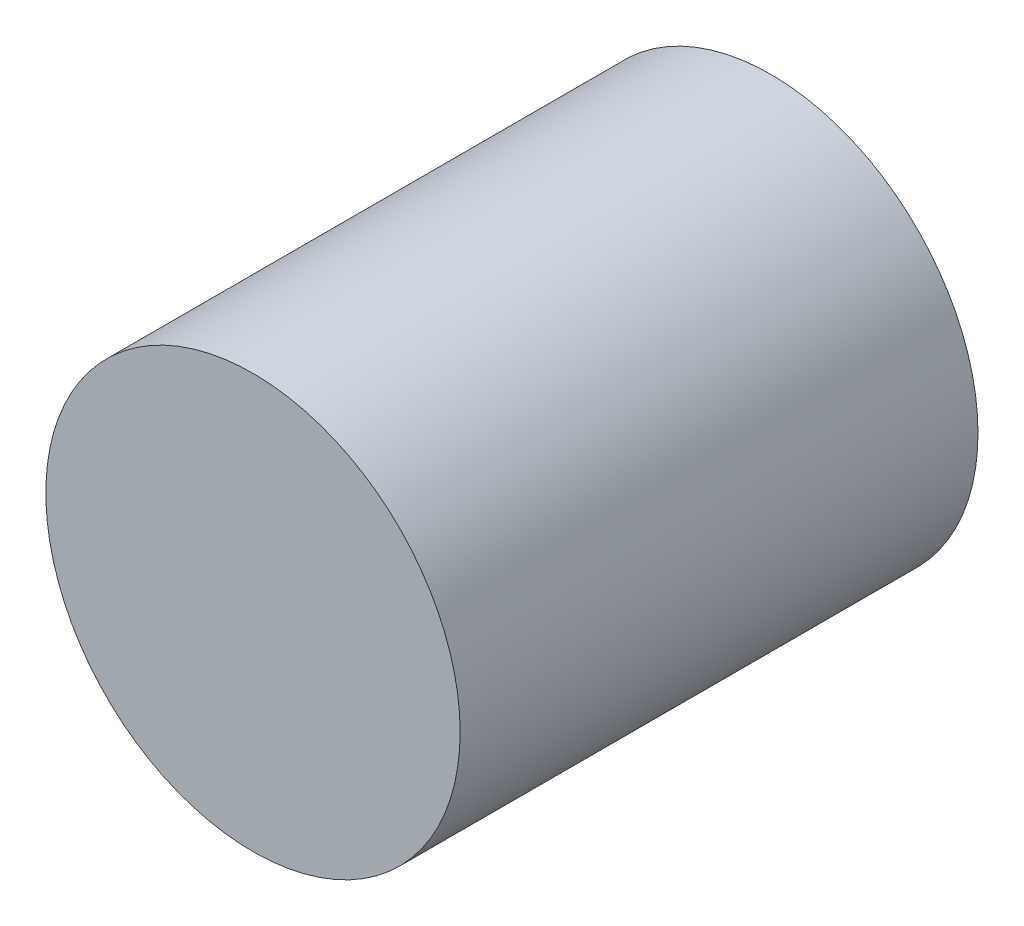
SolidWorks part; units mm, degrees
ref_plane "Front Plane" through (0, 0, 0) normal (0, 0, 1) x (1, 0, 0)
ref_plane "Top Plane" through (0, 0, 0) normal (0, 1, 0) x (1, 0, 0)
ref_plane "Right Plane" through (0, 0, 0) normal (1, 0, 0) x (0, 0, -1)
sketch "Sketch1" plane through (0, 0, 0) normal (0, 0, 1) x (1, 0, 0)
  circle A0 centre (0, 0) radius 6
  dimension "D1" = 12
extrude "RollerExtrude" add sketch "Sketch1" along normal blind 15
